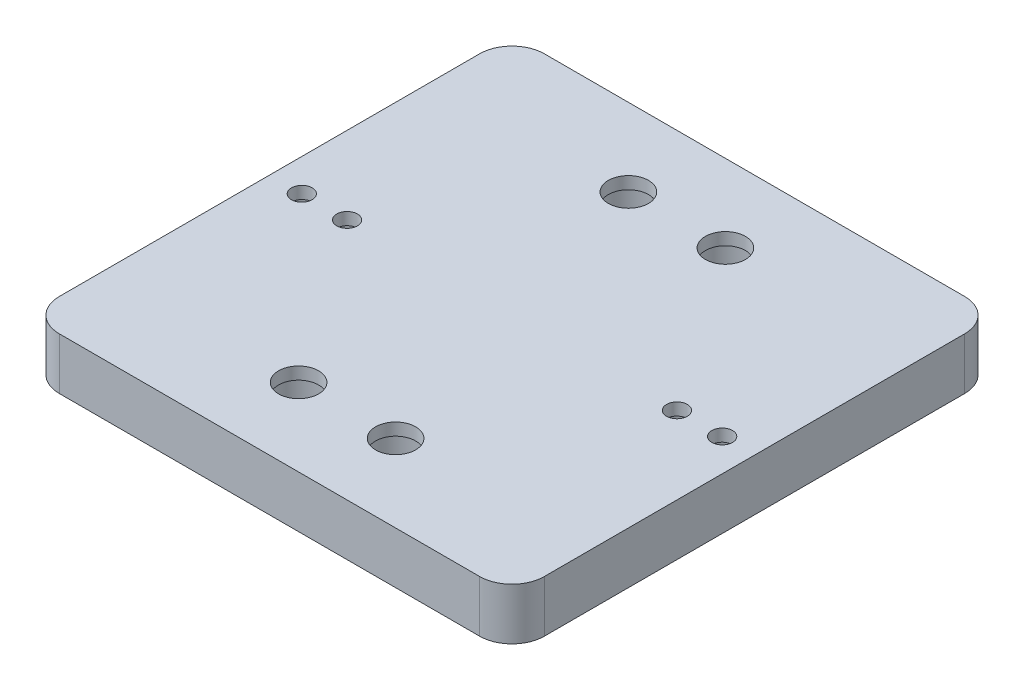
SolidWorks part; units mm, degrees
ref_plane "Front Plane" through (0, 0, 0) normal (0, 0, 1) x (1, 0, 0)
ref_plane "Top Plane" through (0, 0, 0) normal (0, 1, 0) x (1, 0, 0)
ref_plane "Right Plane" through (0, 0, 0) normal (1, 0, 0) x (0, 0, -1)
sketch "Sketch1" plane through (0, 0, 0) normal (0, 1, 0) x (1, 0, 0)
  line L0 (0, 37.5) -> (0, -37.5) construction
  line L1 (-37.5, 37.5) -> (37.5, 37.5)
  line L2 (-37.5, 37.5) -> (-37.5, -37.5)
  line L3 (-37.5, -37.5) -> (37.5, -37.5)
  line L4 (37.5, 37.5) -> (37.5, -37.5)
  line L5 (-37.5, 0) -> (37.5, 0) construction
  line L6 (-37.5, 0) -> (-20.5, 0) construction
  line L15 (-37.5, 5) -> (-20.5, 5) construction
  line L16 (-37.5, 5) -> (-37.5, -5) construction
  line L17 (-37.5, -5) -> (-20.5, -5) construction
  line L18 (-20.5, 5) -> (-20.5, -5) construction
  line L19 (-29, 5) -> (-29, -5) construction
  line L20 (29, 5) -> (29, -5) construction
  line L21 (37.5, 0) -> (20.5, 0) construction
  line L22 (20.5, 5) -> (20.5, -5) construction
  line L23 (37.5, -5) -> (20.5, -5) construction
  line L24 (37.5, 5) -> (37.5, -5) construction
  line L25 (37.5, 5) -> (20.5, 5) construction
  line L26 (-15, -25.5) -> (15, -25.5) construction
  line L27 (-15, -13.5) -> (15, -13.5) construction
  line L28 (-15, -13.5) -> (-15, -37.5) construction
  line L29 (-15, -37.5) -> (15, -37.5) construction
  line L30 (15, -13.5) -> (15, -37.5) construction
  line L31 (0, -13.5) -> (0, -37.5) construction
  line L32 (0, 13.5) -> (0, 37.5) construction
  line L33 (-15, 25.5) -> (15, 25.5) construction
  line L34 (15, 13.5) -> (15, 37.5) construction
  line L35 (-15, 37.5) -> (15, 37.5) construction
  line L36 (-15, 13.5) -> (-15, 37.5) construction
  line L37 (-15, 13.5) -> (15, 13.5) construction
  circle A2 centre (-32.5, 0) radius 1.6
  circle A3 centre (-25.5, 0) radius 1.6
  circle A4 centre (25.5, 0) radius 1.6
  circle A5 centre (32.5, 0) radius 1.6
  circle A6 centre (-7.5, -25.5) radius 3.1
  circle A7 centre (7.5, -25.5) radius 3.1
  circle A8 centre (7.5, 25.5) radius 3.1
  circle A9 centre (-7.5, 25.5) radius 3.1
  point P4 (0, 37.5)
  point P6 (-37.5, 0)
  point P19 (-29, 0)
  point P41 (29, 0)
  point P48 (0, -25.5)
  point P62 (0, 25.5)
  dimension "D1" = 10
  dimension "D2" = 3.2
  dimension "D3" = 5
  dimension "D4" = 7
  dimension "D5" = 6.2
  dimension "D7" = 15
  dimension "D6" = 30
  dimension "D8" = 12
  dimension "D9" = 75
extrude "Boss-Extrude1" add sketch "Sketch1" along normal blind 4
sketch "Sketch3" plane through (0, 0, 0) normal (0, -1, 0) x (1, 0, 0)
  line L0 (-37.5, -37.5) -> (-37.5, 37.5) construction
  line L1 (37.5, -37.5) -> (-37.5, -37.5) construction
  line L2 (37.5, 37.5) -> (37.5, -37.5) construction
  line L3 (-37.5, 37.5) -> (37.5, 37.5) construction
  line L4 (-37.5, -37.5) -> (-37.5, 37.5)
  line L5 (37.5, -37.5) -> (-37.5, -37.5)
  line L6 (37.5, 37.5) -> (37.5, -37.5)
  line L7 (-37.5, 37.5) -> (37.5, 37.5)
  circle A0 centre (-7.5, -25.5) radius 3.1 construction
  circle A1 centre (7.5, -25.5) radius 3.1 construction
  circle A2 centre (32.5, 0) radius 1.6 construction
  circle A3 centre (25.5, 0) radius 1.6 construction
  circle A4 centre (7.5, 25.5) radius 3.1 construction
  circle A5 centre (-7.5, 25.5) radius 3.1 construction
  circle A6 centre (-25.5, 0) radius 1.6 construction
  circle A7 centre (-32.5, 0) radius 1.6 construction
  circle A8 centre (-7.5, -25.5) radius 3.1
  circle A9 centre (7.5, -25.5) radius 3.1
  circle A10 centre (32.5, 0) radius 1.6
  circle A11 centre (25.5, 0) radius 1.6
  circle A12 centre (7.5, 25.5) radius 3.1
  circle A13 centre (-7.5, 25.5) radius 3.1
  circle A14 centre (-25.5, 0) radius 1.6
  circle A15 centre (-32.5, 0) radius 1.6
extrude "Boss-Extrude2" add sketch "Sketch3" along normal blind 4
sketch "Sketch5" plane through (0, -4, 0) normal (0, -1, 0) x (1, 0, 0)
  line L0 (0, 37.5) -> (0, -37.5) construction
  line L1 (37.5, 37.5) -> (-37.5, 37.5) construction
  line L2 (-37.5, -37.5) -> (37.5, -37.5) construction
  line L3 (-37.5, 0) -> (37.5, 0) construction
  line L4 (-37.5, 37.5) -> (-37.5, -37.5) construction
  line L5 (37.5, -37.5) -> (37.5, 37.5) construction
  circle A0 centre (-7.5, -25.5) radius 5.05
  circle A1 centre (7.5, -25.5) radius 5.05
  circle A2 centre (7.5, 25.5) radius 5.05
  circle A3 centre (-7.5, 25.5) radius 5.05
  circle A4 centre (-32.5, 0) radius 2.95
  circle A5 centre (-25.5, 0) radius 2.95
  circle A6 centre (25.5, 0) radius 2.95
  circle A7 centre (32.5, 0) radius 2.95
  dimension "D1" = 10.1
  dimension "D2" = 5.9
  dimension "D3" = 5.9
extrude "Cut-Extrude1" cut sketch "Sketch5" against normal blind 6.1
ref_plane "Plane1" through (0, -4, 0) normal (0, -1, 0) x (-1, 0, 0)
fillet "Fillet2" radius 5 4 edges at (37.5, 0, 37.5) (37.5, 0, -37.5) (-37.5, 0, -37.5) (-37.5, 0, 37.5)
